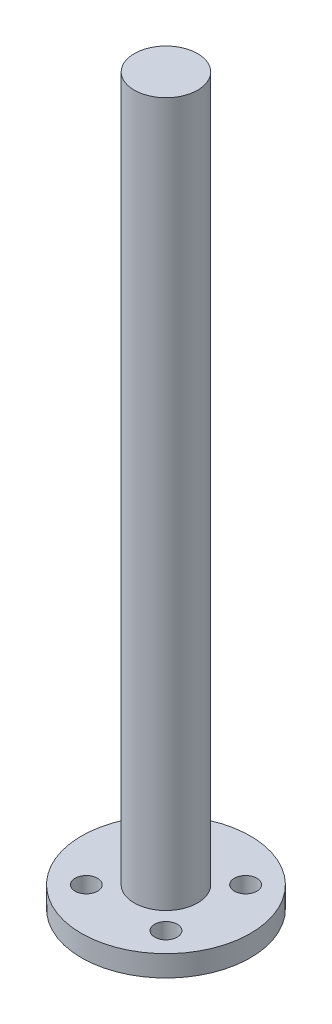
SolidWorks part; units mm, degrees
ref_plane "前视基准面" through (0, 0, 0) normal (0, 0, 1) x (1, 0, 0)
ref_plane "上视基准面" through (0, 0, 0) normal (0, 1, 0) x (1, 0, 0)
ref_plane "右视基准面" through (0, 0, 0) normal (1, 0, 0) x (0, 0, -1)
sketch "草图1" plane through (0, 0, 0) normal (0, 1, 0) x (1, 0, 0)
  line L0 (-14.4048, 0) -> (14.4048, 0) construction
  line L1 (0, 10.6465) -> (0, -10.6465) construction
  line L2 (0, 0) -> (5.6569, -5.6569) construction
  circle A0 centre (0, 0) radius 12
  circle A1 centre (0, 0) radius 8 construction
  circle A2 centre (5.6569, -5.6569) radius 1.6
  circle A3 centre (-5.6559, -5.6559) radius 1.6
  circle A4 centre (-5.6549, 5.6569) radius 1.6
  circle A5 centre (5.6579, 5.6559) radius 1.6
  point P6 (0, 0)
  point P9 (0, 0)
  point P21 (0.001, 0)
  dimension "D1" = 24
  dimension "D2" = 16
  dimension "D3" = 3.2
  dimension "D5" = 4
  dimension "D4" = 45
extrude "凸台-拉伸2" add sketch "草图1" against normal blind 3 contours A0
sketch "草图2" plane through (0, 0, 0) normal (0, 1, 0) x (1, 0, 0)
  line L0 (-16.5349, 0) -> (16.5349, 0) construction
  line L1 (0, 0) -> (5.6569, -5.6569) construction
  circle A0 centre (0, 0) radius 8 construction
  circle A1 centre (5.6569, -5.6569) radius 1.6
  circle A2 centre (-5.6569, -5.6569) radius 1.6
  circle A3 centre (-5.6569, 5.6569) radius 1.6
  circle A4 centre (5.6569, 5.6569) radius 1.6
  point P6 (0, 0)
  point P17 (0, 0)
  dimension "D1" = 16
  dimension "D2" = 3.2
  dimension "D3" = 45
  dimension "D4" = 4
extrude "切除-拉伸1" cut sketch "草图2" against normal blind 3
sketch "草图3" plane through (0, 0, 0) normal (0, 1, 0) x (1, 0, 0)
  circle A0 centre (0, 0) radius 4.5
  dimension "D1" = 9
extrude "凸台-拉伸3" add sketch "草图3" along normal blind 100
